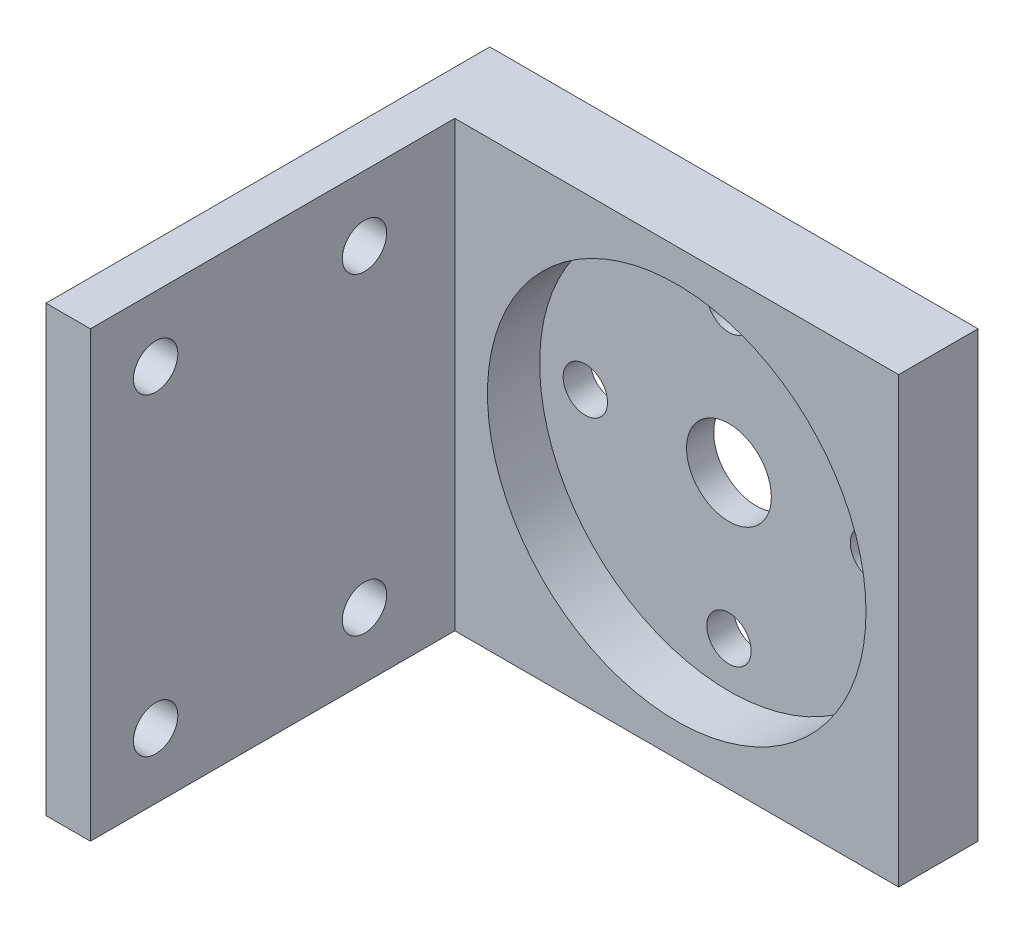
SolidWorks part; units mm, degrees
material "ABS"
ref_plane "Front Plane" through (0, 0, 0) normal (1, 0, 0) x (0, 1, 0)
ref_plane "Top Plane" through (0, 0, 0) normal (0, 0, 1) x (0, 1, 0)
ref_plane "Right Plane" through (0, 0, 0) normal (0, 1, 0) x (-1, 0, 0)
sketch "Sketch1" plane through (0, 0, 0) normal (0, 0, 1) x (0, 1, 0)
  line L1 (0, 0) -> (34, 0)
  line L2 (0, 0) -> (0, 34)
  line L3 (0, 34) -> (34, 34)
  line L4 (34, 0) -> (34, 34)
  dimension "D1" = 34
  dimension "D2" = 34
extrude "Boss-Extrude1" add sketch "Sketch1" along normal blind 6.08
sketch "Sketch2" plane through (-34, 0, 0) normal (-1, 0, 0) x (0, -1, 0)
  line L1 (0, 0) -> (-34, 0)
  line L2 (0, 0) -> (0, 34)
  line L3 (0, 34) -> (-34, 34)
  line L4 (-34, 0) -> (-34, 34)
  dimension "D1" = 34
  dimension "D2" = 34
extrude "Boss-Extrude2" add sketch "Sketch2" along normal blind 3.4
hole_wizard "Hole1" positions "Sketch3" profile "Sketch4" legacy end condition through all
sketch "Sketch3" plane through (-34, 0, 0) normal (1, 0, 0) x (0, 1, 0)
  line L1 (0, 6.08) -> (0, 34) construction
  line L2 (0, 34) -> (34, 34) construction
  point P0 (5, 29)
  point P4 (29, 29)
  point P11 (5, 13)
  point P13 (29, 13)
  dimension "D1" = 16
  dimension "D2" = 24
  dimension "D3" = 5
  dimension "D4" = 5
sketch "Sketch4" plane through (-34, 5, 29) normal (0, 1, 0) x (0, 0, -1)
  line L0 (0, 0) -> (0, 3.4)
  line L1 (0, 3.4) -> (1.7, 3.4)
  line L2 (1.7, 3.4) -> (1.7, 0)
  line L3 (1.7, 0) -> (0, 0)
  line L4 (0, 110) -> (0, -10) construction
  dimension "Diameter" = 3.4
  dimension "Depth" = 3.4
sketch "Sketch5" plane through (0, 0, 6.08) normal (0, 0, 1) x (1, 0, 0)
  line L0 (0, 0) -> (0, 34) construction
  line L1 (-34, 0) -> (0, 0) construction
  circle A0 centre (-17, 17) radius 14.5
  dimension "D1" = 29
  dimension "D2" = 17
  dimension "D3" = 17
extrude "Cut-Extrude1" cut sketch "Sketch5" against normal blind 4
hole_wizard "M3 Clearance Hole1" positions "Sketch6" profile "Sketch8" hole size "M3" standard "ANSI Metric" end condition through all
sketch "Sketch6" plane through (0, 0, 2.08) normal (0, 0, 1) x (0, -1, 0)
  circle A1 centre (-17, -17) radius 14.5 construction
  circle A2 centre (-17, -17) radius 14.5 construction
  point P0 (-17, -6)
  point P6 (-6, -17)
  point P7 (-17, -28)
  point P8 (-28, -17)
  point P14 (0, 0)
  point P15 (0, 0)
  point P16 (-25.9924, -18.6723)
  point P17 (-29.2019, -16.9569)
  point P20 (0, 0)
  dimension "D3" = 11
  dimension "D2" = 11
  dimension "D4" = 22
  dimension "D1" = 4
sketch "Sketch8" plane through (-6, 17, 2.08) normal (1, 0, 0) x (0, -1, 0)
  line L0 (0, 0) -> (0, 2.08)
  line L1 (0, 2.08) -> (1.7, 2.08)
  line L2 (1.7, 2.08) -> (1.7, 0)
  line L5 (1.7, 0) -> (0, 0)
  line L11 (0, -6.35) -> (0, 107.95) construction
  dimension "Thru Hole Dia." = 3.4
  dimension "Thru Hole Depth" = 2.08
hole_wizard "Hole2" positions "Sketch9" profile "Sketch10" legacy end condition through all
sketch "Sketch9" plane through (0, 0, 2.08) normal (0, 0, 1) x (0, -1, 0)
  circle A0 centre (-17, -17) radius 14.5 construction
  point P0 (-17, -17)
sketch "Sketch10" plane through (-17, 17, 2.08) normal (1, 0, 0) x (0, -1, 0)
  line L0 (0, 0) -> (0, 2.08)
  line L1 (0, 2.08) -> (3.25, 2.08)
  line L2 (3.25, 2.08) -> (3.25, 0)
  line L3 (3.25, 0) -> (0, 0)
  line L4 (0, 110) -> (0, -10) construction
  dimension "Diameter" = 6.5
  dimension "Depth" = 2.08
equation "\"L\"= 32"
equation "\"center\"= \"L\" / 2"
